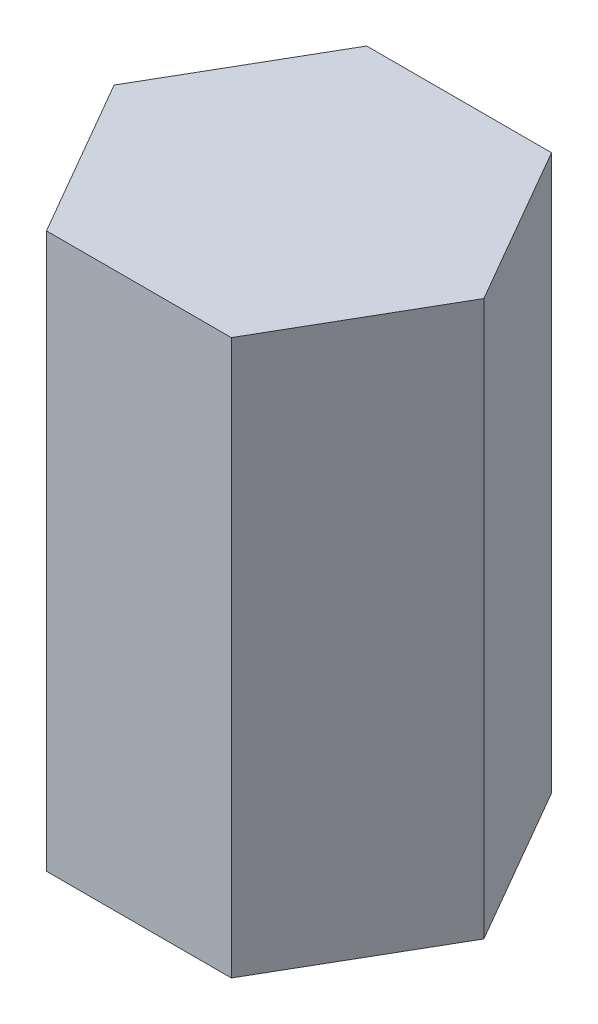
SolidWorks part; units mm, degrees
ref_plane "Alzado" through (0, 0, 0) normal (0, 0, 1) x (1, 0, 0)
ref_plane "Planta" through (0, 0, 0) normal (0, 1, 0) x (1, 0, 0)
ref_plane "Vista lateral" through (0, 0, 0) normal (1, 0, 0) x (0, 0, -1)
sketch "Croquis_hexagono" plane through (0, 0, 0) normal (0, 1, 0) x (1, 0, 0)
  line L1 (40, 0) -> (20, 34.641)
  line L2 (20, 34.641) -> (-20, 34.641)
  line L3 (-20, 34.641) -> (-40, 0)
  line L4 (-40, 0) -> (-20, -34.641)
  line L5 (-20, -34.641) -> (20, -34.641)
  line L6 (20, -34.641) -> (40, 0)
  circle A0 centre (0, 0) radius 40 construction
  dimension "D1" = 80
extrude "Prisma_hexagonal" add sketch "Croquis_hexagono" along normal blind 120
sketch "Croquis_agujeros_montaje" plane through (0, 0, 0) normal (0, 1, 0) x (1, 0, 0)
  circle A0 centre (0, 0) radius 4
  dimension "D1" = 8
extrude "Agujero_inserto_M6" cut sketch "Croquis_agujeros_montaje" along normal blind 14
